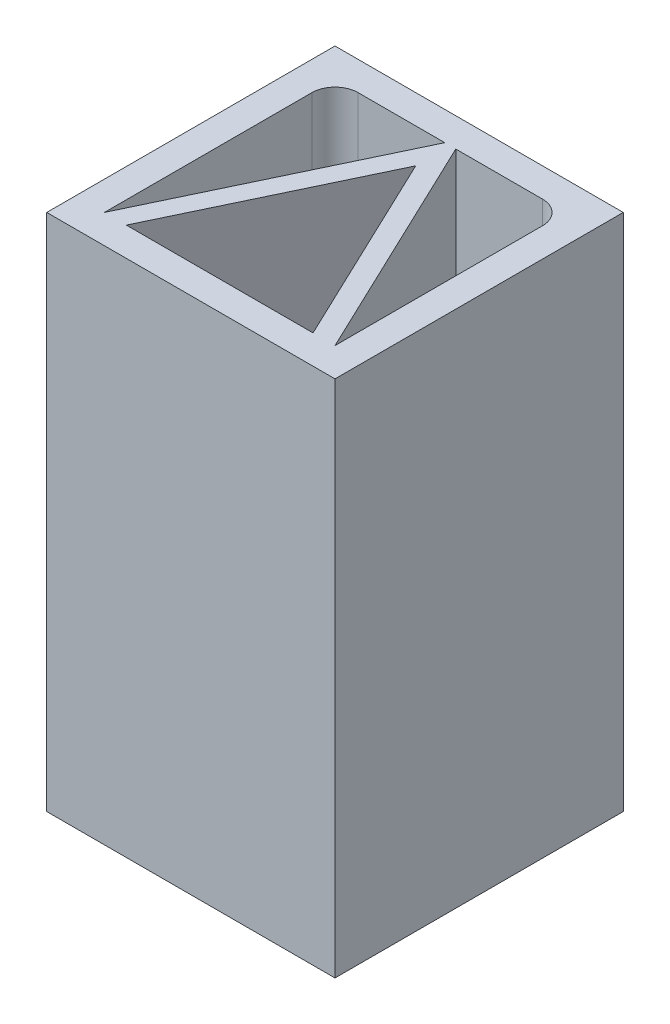
SolidWorks part; units mm, degrees
ref_plane "Front Plane" through (0, 0, 0) normal (0, 0, 1) x (1, 0, 0)
ref_plane "Top Plane" through (0, 0, 0) normal (0, 1, 0) x (1, 0, 0)
ref_plane "Right Plane" through (0, 0, 0) normal (1, 0, 0) x (0, 0, -1)
sketch "Sketch1" plane through (0, 0, 0) normal (0, 1, 0) x (1, 0, 0)
  line L0 (12.5, 25) -> (12.5, 22.5) construction
  line L1 (0, 0) -> (25, 0)
  line L2 (0, 0) -> (0, 25)
  line L3 (0, 25) -> (25, 25)
  line L4 (25, 0) -> (25, 25)
  line L5 (2.5, 22.5) -> (22.5, 22.5)
  line L6 (2.5, 22.5) -> (2.5, 2.5)
  line L7 (2.5, 2.5) -> (22.5, 2.5)
  line L8 (22.5, 22.5) -> (22.5, 2.5)
  line L9 (0, 12.5) -> (2.5, 12.5) construction
  dimension "D1" = 25
  dimension "D2" = 25
  dimension "D3" = 2.5
  dimension "D4" = 2.5
extrude "Boss-Extrude1" add sketch "Sketch1" along normal blind 45
sketch "Sketch3" plane through (0, 0, 0) normal (0, -1, 0) x (1, 0, 0)
  line L0 (22.5, -2.5) -> (12.5, -23.5)
  line L2 (12.5, -23.5) -> (2.5, -2.5)
  line L3 (12.5, -23.5) -> (12.5, -2.5) construction
  line L4 (2.5, -2.5) -> (22.5, -2.5) construction
  line L5 (22.5, -2.5) -> (20.5952, -2.5)
  line L6 (20.5952, -2.5) -> (12.5, -19.5)
  line L7 (12.5, -19.5) -> (4.4048, -2.5)
  line L8 (4.4048, -2.5) -> (2.5, -2.5)
  line L9 (22.5, -22.5) -> (2.5, -22.5) construction
  point P3 (12.5, -23.5225)
  point P13 (0, 0)
  dimension "D1" = 4
  dimension "D2" = 1
extrude "Boss-Extrude4" add sketch "Sketch3" against normal through all
fillet "Fillet2" radius 2 2 edges at (2.5, 22.5, -22.5) (22.5, 22.5, -22.5)
